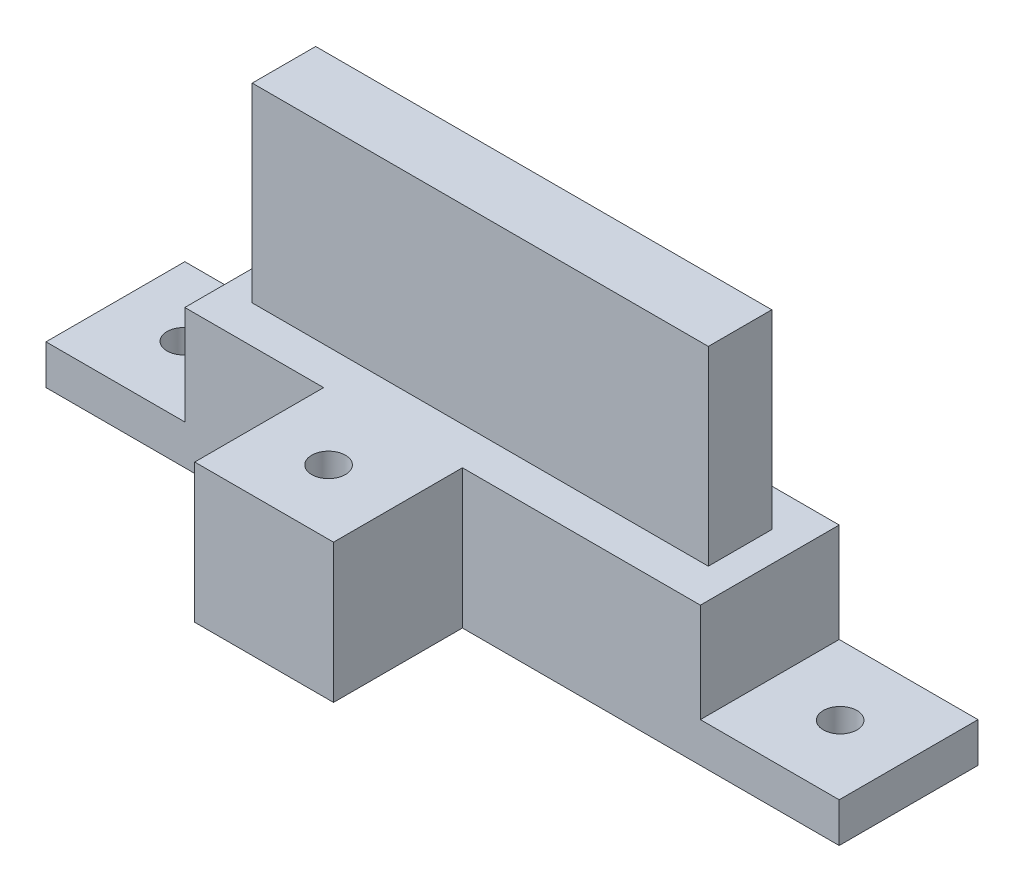
SolidWorks part; units mm, degrees
ref_plane "Front Plane" through (0, 0, 0) normal (0, 0, 1) x (1, 0, 0)
ref_plane "Top Plane" through (0, 0, 0) normal (0, 1, 0) x (1, 0, 0)
ref_plane "Right Plane" through (0, 0, 0) normal (1, 0, 0) x (0, 0, -1)
sketch "Sketch1" plane through (0, 0, 0) normal (0, 0, 1) x (1, 0, 0)
  line L0 (-100, 0) -> (100, 0)
  line L1 (100, 0) -> (100, 10)
  line L2 (100, 10) -> (65, 10)
  line L3 (65, 10) -> (65, 35)
  line L4 (65, 35) -> (57.5, 35)
  line L5 (57.5, 35) -> (57.5, 83)
  line L6 (57.5, 83) -> (-57.5, 83)
  line L7 (0, 83) -> (0, 0) construction
  line L8 (-57.5, 35) -> (-57.5, 83)
  line L9 (-65, 35) -> (-57.5, 35)
  line L10 (-65, 10) -> (-65, 35)
  line L11 (-100, 10) -> (-65, 10)
  line L12 (-100, 0) -> (-100, 10)
  dimension "D1" = 10
  dimension "D2" = 200
  dimension "D3" = 130
  dimension "D4" = 35
  dimension "D5" = 83
  dimension "D6" = 115
extrude "Boss-Extrude1" add sketch "Sketch1" along normal mid plane 35
sketch "Sketch4" plane through (0, 83, 0) normal (0, 1, 0) x (1, 0, 0)
  line L0 (-57.5, -17.5) -> (-57.5, 17.5) construction
  line L1 (-57.5, 8) -> (57.5, 8)
  line L2 (-57.5, 8) -> (-57.5, -8)
  line L3 (-57.5, -8) -> (57.5, -8)
  line L4 (57.5, 8) -> (57.5, -8)
  line L5 (57.5, -17.5) -> (57.5, 17.5) construction
  dimension "D1" = 16
extrude "Cut-Extrude1" cut sketch "Sketch4" against normal up to surface (48 mm away) flip side to cut up to face at (61.25, 35, 0)
sketch "Sketch5" plane through (0, 0, 0) normal (0, 0, 1) x (1, 0, 0)
  line L0 (-100, 0) -> (100, 0) construction
  line L1 (-30, 35) -> (5, 35)
  line L2 (-30, 35) -> (-30, 0)
  line L3 (-30, 0) -> (5, 0)
  line L4 (5, 35) -> (5, 0)
  line L5 (-65, 35) -> (-57.5, 35) construction
  line L6 (-65, 10) -> (-65, 35) construction
  dimension "D1" = 35
  dimension "D2" = 35
extrude "Boss-Extrude2" add sketch "Sketch5" along normal mid plane 100
sketch "Sketch6" plane through (0, 35, 0) normal (0, 1, 0) x (1, 0, 0)
  line L0 (5, -50) -> (5, -17.5) construction
  line L1 (5, -50) -> (-30, -50) construction
  line L2 (-100, 0) -> (-65, 0) construction
  line L3 (-100, -17.5) -> (-100, 17.5) construction
  line L4 (100, 0) -> (65, 0) construction
  line L5 (0, 0) -> (25.0601, 0) construction
  circle A0 centre (-12.5, -33.75) radius 4.25
  circle A1 centre (-82.75, 0) radius 4.25
  circle A2 centre (82.75, 0) radius 4.25
  circle A3 centre (-12.5, 33.75) radius 4.25
  point P6 (5, -33.75)
  point P9 (-12.5, -50)
  dimension "D1" = 8.5
  dimension "D3" = 13
  dimension "D2" = 13
extrude "Cut-Extrude2" cut sketch "Sketch6" against normal through all
